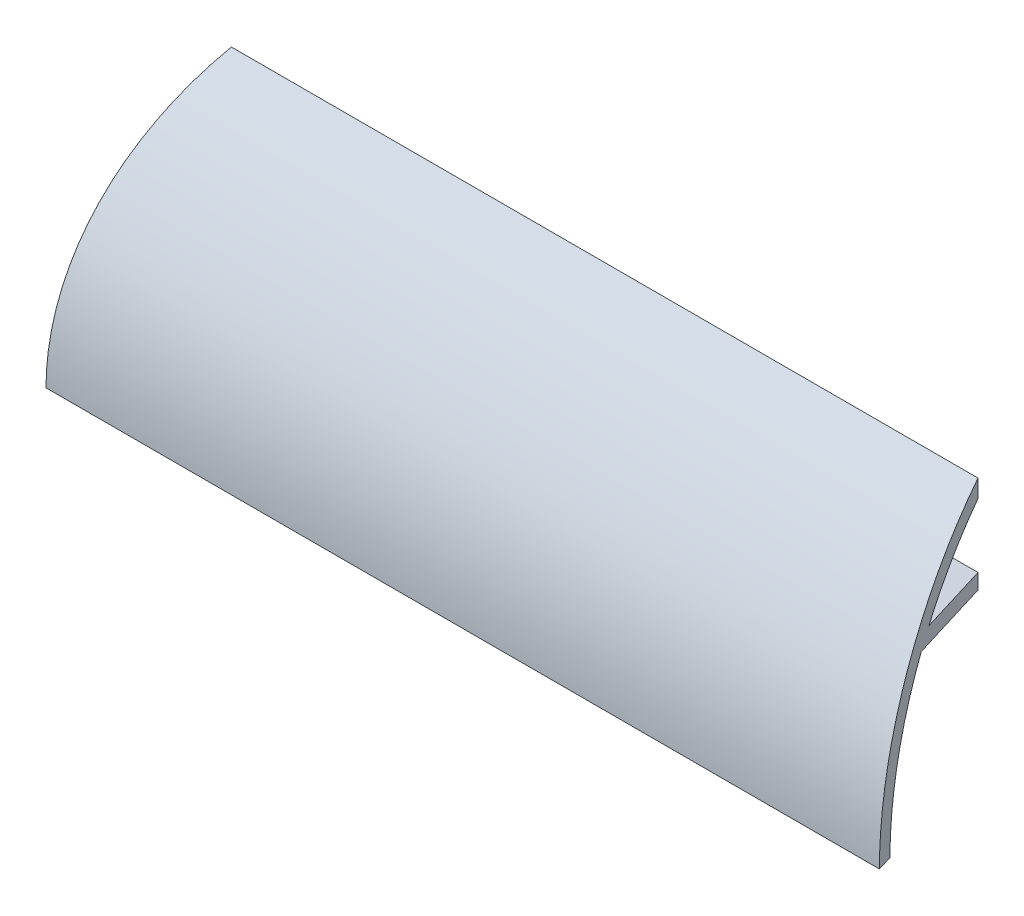
SolidWorks part; units mm, degrees
ref_plane "Front Plane" through (0, 0, 0) normal (0, 0, 1) x (1, 0, 0)
ref_plane "Top Plane" through (0, 0, 0) normal (0, 1, 0) x (1, 0, 0)
ref_plane "Right Plane" through (0, 0, 0) normal (1, 0, 0) x (0, 0, -1)
sketch "Sketch1" plane through (0, 0, 0) normal (1, 0, 0) x (0, 0, -1)
  line L0 (0, 0) -> (0.24, 0)
  line L1 (2.24, 3.6002) -> (2.24, 3.88)
  line L2 (0.24, 0) -> (0.24, 2.5602) construction
  line L3 (0.9507, 2.35) -> (2.24, 2.35)
  line L4 (2.24, 2.35) -> (2.24, 2.59)
  line L5 (2.24, 2.59) -> (1.1229, 2.59)
  arc A0 (0.24, 0) -> (0.9507, 2.35) centre (4.4804, 0) cw
  arc A1 (0, 0) -> (2.24, 3.88) centre (4.4804, 0) cw
  arc A2 (1.1229, 2.59) -> (2.24, 3.6002) centre (4.4804, 0) cw
  dimension "D1" = 0.24
  dimension "D2" = 3.88
  dimension "D3" = 2.24
  dimension "D4" = 0.24
  dimension "D5" = 2.59
extrude "Boss-Extrude1" add sketch "Sketch1" along normal blind 13.15
sketch "Sketch2" plane through (0, 0, 0) normal (0, 1, 0) x (1, 0, 0)
  line L1 (0.9172, 3) -> (12.2328, 3)
  line L3 (0, 0) -> (13.15, 0)
  line L4 (12.2328, 3) -> (13.15, 0)
  line L6 (0.9172, 3) -> (0, 0)
  dimension "D2" = 73
  dimension "D3" = 3
  dimension "D4" = 73
extrude "Cut-Extrude2" cut sketch "Sketch2" against normal blind 13 and the other way through all flip side to cut contours L3 L4 L1 L6
